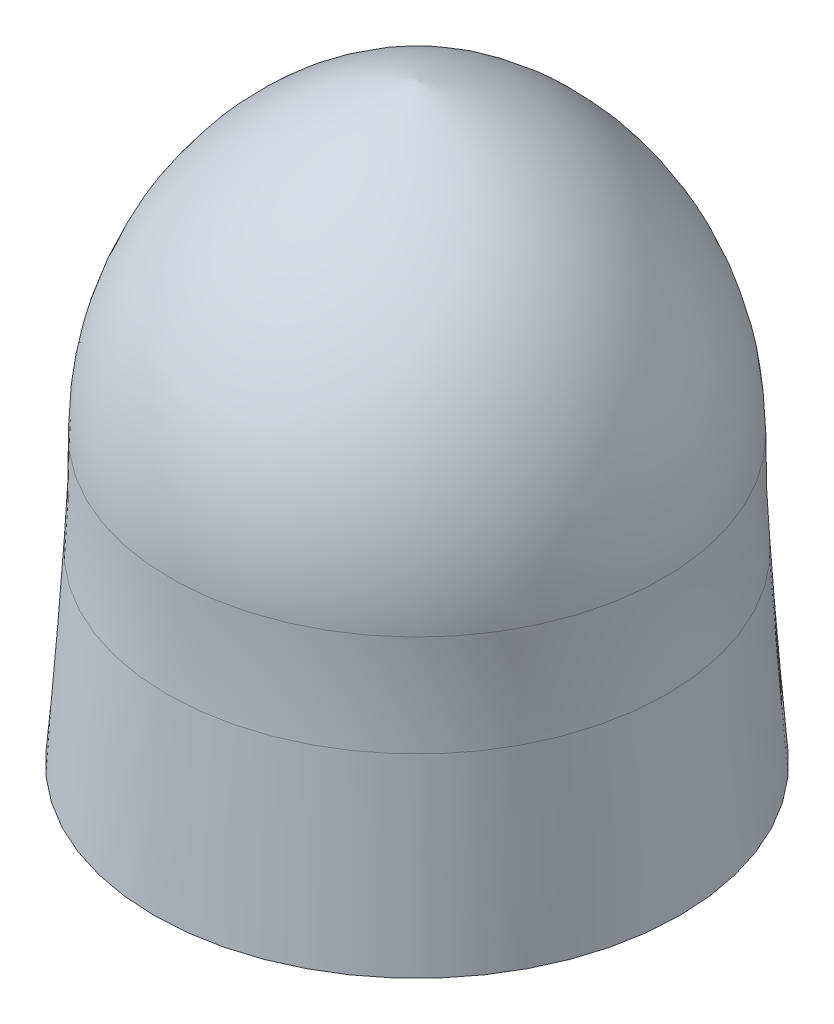
SolidWorks part; units mm, degrees
ref_plane "Front Plane" through (0, 0, 0) normal (0, 0, 1) x (1, 0, 0)
ref_plane "Top Plane" through (0, 0, 0) normal (0, 1, 0) x (1, 0, 0)
ref_plane "Right Plane" through (0, 0, 0) normal (1, 0, 0) x (0, 0, -1)
sketch "Sketch1" plane through (0, 0, 0) normal (0, 0, 1) x (1, 0, 0)
  line L0 (0, 0) -> (0, -90) construction
  line L1 (-37.2972, -51.3476) -> (-40, -90)
  line L2 (-40, -90) -> (0, -90)
  line L3 (0, 0) -> (0, -90)
  arc A0 (0, 0) -> (-37.2972, -51.3476) centre (10, -46.4832) ccw
  point P5 (0, 0)
  dimension "D1" = 10
  dimension "D2" = 4
  dimension "D3" = 40
  dimension "D4" = 90
revolve "Revolve2" add sketch "Sketch1" angle 360 about L0
fillet "Fillet1" radius 200 1 edges at (-37.2972, -51.3476, 0)
